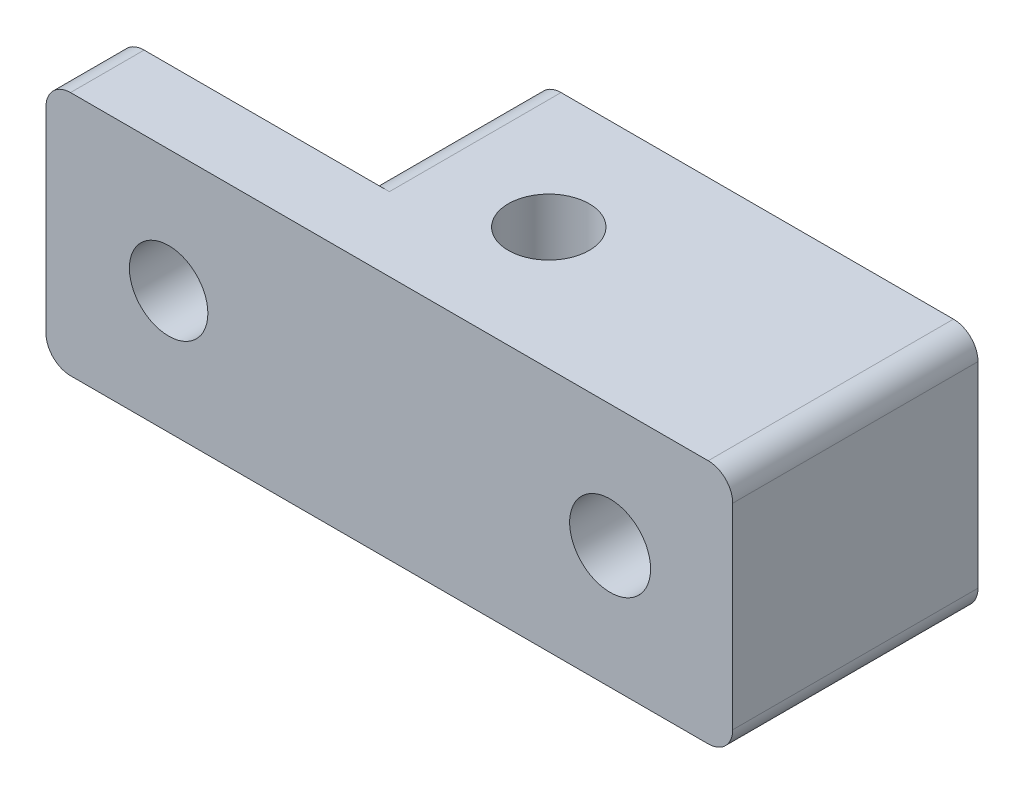
SolidWorks part; units mm, degrees
material "5052-H34"
ref_plane "正面" through (0, 0, 0) normal (0, 0, 1) x (1, 0, 0)
ref_plane "平面" through (0, 0, 0) normal (0, 1, 0) x (1, 0, 0)
ref_plane "右側面" through (0, 0, 0) normal (1, 0, 0) x (0, 0, -1)
sketch "ｽｹｯﾁ1" plane through (0, 0, 0) normal (0, 0, 1) x (1, 0, 0)
  line L0 (0, 0) -> (-18, 0) construction
  line L2 (-23, 5) -> (5, 5)
  line L3 (-23, 5) -> (-23, -5)
  line L4 (-23, -5) -> (5, -5)
  line L5 (5, 5) -> (5, -5)
  line L6 (-23, 5) -> (5, -5) construction
  line L7 (-23, -5) -> (5, 5) construction
  circle A0 centre (0, 0) radius 1.65
  circle A1 centre (-18, 0) radius 1.6
  point P4 (-9, 0)
  dimension "D1" = 3.3
  dimension "D3" = 3.2
  dimension "D2" = 18
  dimension "D4" = 10
  dimension "D5" = 28
extrude "ﾎﾞｽ - 押し出し1" add sketch "ｽｹｯﾁ1" along normal blind 10
sketch "ｽｹｯﾁ2" plane through (0, 5, 0) normal (0, 1, 0) x (1, 0, 0)
  line L0 (5, -5) -> (-7.5, -5) construction
  line L1 (5, -10) -> (5, 0) construction
  circle A0 centre (-7.5, -5) radius 1.65
  dimension "D1" = 3.3
  dimension "D2" = 12.5
extrude "ｶｯﾄ - 押し出し1" cut sketch "ｽｹｯﾁ2" against normal through all
sketch "ｽｹｯﾁ3" plane through (0, 0, 0) normal (0, 0, -1) x (-1, 0, 0)
  line L1 (13, -5) -> (23, -5)
  line L2 (13, -5) -> (13, 5)
  line L3 (13, 5) -> (23, 5)
  line L4 (-5, 5) -> (-5, -5)
  line L5 (-5, -5) -> (23, -5)
  line L6 (23, -5) -> (23, 5)
  line L7 (23, 5) -> (-5, 5)
  line L8 (-5, 5) -> (-5, -5)
  line L9 (-5, -5) -> (23, -5)
  line L10 (23, -5) -> (23, 5)
  line L11 (23, 5) -> (-5, 5)
  line L12 (23, -5) -> (23, 5)
  line L13 (13, -5) -> (23, 5) construction
  line L14 (13, 5) -> (23, -5) construction
  point P0 (18, 0)
  dimension "D2" = 0
extrude "ｶｯﾄ - 押し出し2" cut sketch "ｽｹｯﾁ3" against normal blind 7
fillet "ﾌｨﾚｯﾄ1" radius 1 6 edges at (5, -5, 5) (5, 5, 5) (-23, 5, 8.5) (-23, -5, 8.5) (-13, -5, 3.5) (-13, 5, 3.5)
